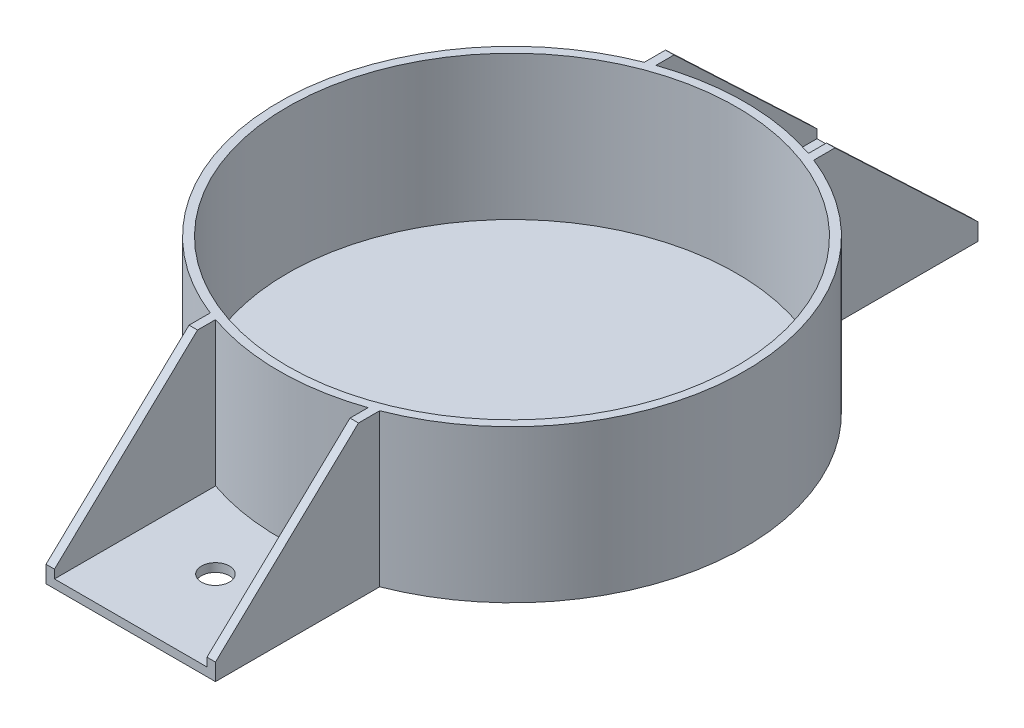
SolidWorks part; units mm, degrees
ref_plane "前视基准面" through (0, 0, 0) normal (0, 0, 1) x (1, 0, 0)
ref_plane "上视基准面" through (0, 0, 0) normal (0, 1, 0) x (1, 0, 0)
ref_plane "右视基准面" through (0, 0, 0) normal (1, 0, 0) x (0, 0, -1)
sketch "草图3" plane through (0, 0, 0) normal (0, 1, 0) x (1, 0, 0)
  line L0 (-40.5841, 0) -> (50.1108, 0) construction
  line L1 (-10, 25.6174) -> (-10, 45)
  line L2 (-10, 45) -> (10, 45)
  line L3 (10, 45) -> (10, 25.6174)
  line L4 (0, -71.165) -> (0, 71.165) construction
  line L5 (10, -45) -> (10, -25.6174)
  line L6 (-10, -45) -> (10, -45)
  line L7 (-10, -25.6174) -> (-10, -45)
  arc A0 (-10, 25.6174) -> (-10, -25.6174) centre (0, 0) ccw
  arc A1 (10, -25.6174) -> (10, 25.6174) centre (0, 0) ccw
  dimension "D1" = 55
  dimension "D2" = 20
  dimension "D3" = 45
extrude "凸台-拉伸2" add sketch "草图3" along normal blind 1
sketch "草图6" plane through (0, 1, 0) normal (0, 1, 0) x (1, 0, 0)
  circle A0 centre (0, 0) radius 27.5
  circle A1 centre (0, 0) radius 26.5
  arc A2 (10, -25.6174) -> (10, 25.6174) centre (0, 0) ccw construction
  dimension "D1" = 1
extrude "凸台-拉伸3" add sketch "草图6" along normal blind 17
sketch "草图8" plane through (0, 0, 45) normal (0, 0, 1) x (1, 0, 0)
  line L0 (26.5, 18) -> (-26.5, 18) construction
  line L1 (-10, 1) -> (-9, 1)
  line L2 (-10, 1) -> (-10, 18)
  line L3 (-10, 18) -> (-9, 18)
  line L4 (-9, 1) -> (-9, 18)
  line L5 (0, 0) -> (0, 20.9746) construction
  line L6 (9, 1) -> (9, 18)
  line L7 (10, 18) -> (9, 18)
  line L8 (10, 1) -> (10, 18)
  line L9 (10, 1) -> (9, 1)
  dimension "D1" = 1
extrude "凸台-拉伸4" add sketch "草图8" against normal up to surface (19.3826 mm away)
sketch "草图9" plane through (-10, 0, 0) normal (-1, 0, 0) x (0, 0, 1)
  line L0 (28.1174, 18) -> (45, 2)
  line L1 (25.6174, 18) -> (45, 18) construction
  line L2 (45, 18) -> (45, 0) construction
  line L3 (45, 2) -> (45, 18)
  line L4 (45, 18) -> (28.1174, 18)
  line L5 (25.6174, 0) -> (45, 0) construction
  line L6 (25.6174, 18) -> (25.6174, 0) construction
  dimension "D1" = 2
  dimension "D2" = 2.5
extrude "切除-拉伸2" cut sketch "草图9" against normal blind 20
mirror "镜向1" about plane through (0, 0, 0) normal (0, 0, 1) of "切除-拉伸2", "凸台-拉伸4"
sketch "草图11" plane through (0, 1, 0) normal (0, 1, 0) x (1, 0, 0)
  line L0 (0, 45) -> (0, 32.0158) construction
  line L1 (9, 45) -> (-9, 45) construction
  line L2 (-34.6757, 0) -> (0, 0) construction
  circle A0 centre (0, 35) radius 1.65
  circle A1 centre (0, -35) radius 1.65
  dimension "D1" = 3.3
  dimension "D2" = 10
extrude "切除-拉伸3" cut sketch "草图11" against normal blind 20
